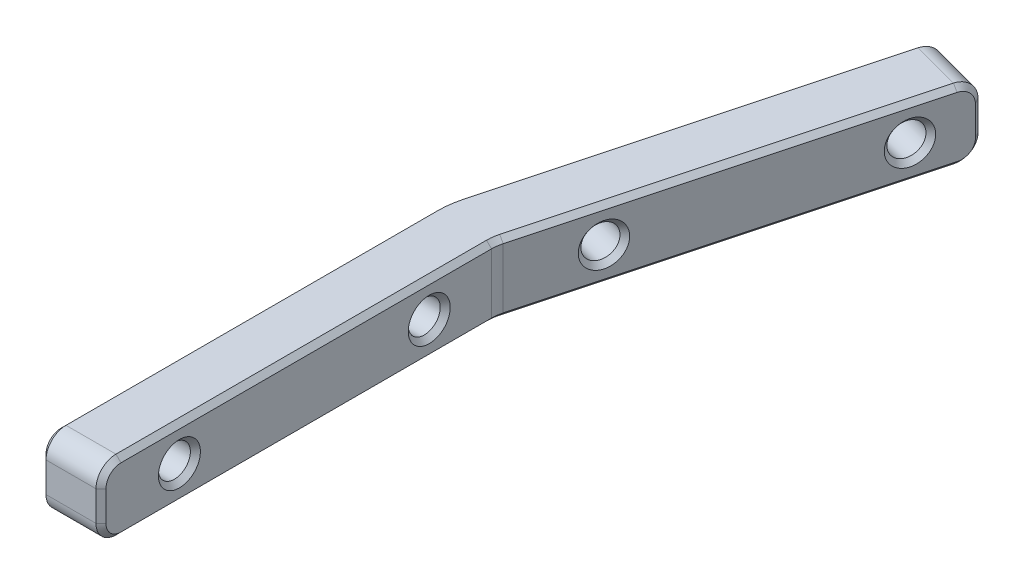
SolidWorks part; units mm, degrees
ref_plane "Front Plane" through (0, 0, 0) normal (0, 0, 1) x (1, 0, 0)
ref_plane "Top Plane" through (0, 0, 0) normal (0, 1, 0) x (1, 0, 0)
ref_plane "Right Plane" through (0, 0, 0) normal (1, 0, 0) x (0, 0, -1)
sketch "Sketch1" plane through (0, 0, 0) normal (0, 1, 0) x (1, 0, 0)
  line L0 (0, 0) -> (0, -50.8) construction
  line L1 (0, 0) -> (13.148, 49.069) construction
  line L2 (3.81, -0.5016) -> (3.81, -50.8)
  line L3 (3.81, -0.5016) -> (16.8282, 48.0829)
  line L4 (-3.81, 0.5016) -> (-3.81, -50.8)
  line L5 (-3.81, 0.5016) -> (9.4678, 50.0551)
  line L6 (3.81, -50.8) -> (-3.81, -50.8)
  line L7 (16.8282, 48.0829) -> (9.4678, 50.0551)
  dimension "D1" = 165
  dimension "D2" = 50.8
  dimension "D3" = 50.8
  dimension "D4" = 3.81
  dimension "D5" = 3.81
extrude "Boss-Extrude1" add sketch "Sketch1" along normal blind 8.89 contours L3 L7 L5 L4 L6 L2
sketch "Sketch2" plane through (3.81, 0, 0) normal (1, 0, 0) x (0, 0, -1)
  line L0 (-50.8, 4.445) -> (-0.5016, 4.445) construction
  line L1 (-50.8, 8.89) -> (-50.8, 0) construction
  line L2 (-0.5016, 8.89) -> (-0.5016, 0) construction
  circle A0 centre (-40.8334, 4.445) radius 2.032
  circle A1 centre (-9.0834, 4.445) radius 2.032
  dimension "D1" = 4.064
  dimension "D2" = 8.5818
  dimension "D3" = 31.75
extrude "Cut-Extrude1" cut sketch "Sketch2" against normal through all contours A1 | A0
sketch "Sketch3" plane through (3.6802, 0, 0.9861) normal (0.9659, 0, 0.2588) x (0.2588, 0, -0.9659)
  line L0 (0.5016, 4.445) -> (50.8, 4.445) construction
  line L1 (50.8, 8.89) -> (50.8, 0) construction
  circle A0 centre (43.3734, 4.445) radius 2.032
  circle A1 centre (11.6234, 4.445) radius 2.032
  dimension "D1" = 11.1218
  dimension "D3" = 4.064
  dimension "D2" = 31.75
extrude "Cut-Extrude2" cut sketch "Sketch3" against normal up to next contours A1 | A0
fillet "Fillet1" radius 2.54 4 edges at (13.148, 0, -49.069) (13.148, 8.89, -49.069) (0, 0, 50.8) (0, 8.89, 50.8)
fillet "Fillet2" radius 5.08 1 edges at (3.81, 4.445, 0.5016)
fillet "Fillet3" radius 11.43 1 edges at (-3.81, 4.445, -0.5016)
chamfer "Chamfer1" distance 0.635 angle 45 32 edges at (7.0198, 4.445, -40.9189) (-1.1977, 4.445, -10.2507) (-3.81, 4.445, 38.8014) (-3.81, 4.445, 7.0514) (-3.7122, 8.89, -0.4887) (2.6949, 8.89, -24.7784) (9.2753, 8.1461, -49.3365) (9.4678, 4.445, -50.0551) (9.2753, 0.7439, -49.3365) (-3.81, 8.89, 24.6316) (-3.81, 8.1461, 50.0561) (-3.81, 4.445, 50.8) (-3.81, 0.7439, 50.0561) (2.6949, 0, -24.7784) (-3.7122, 0, -0.4887) (-3.81, 0, 24.6316) (3.81, 4.445, 38.8014) (3.81, 4.445, 7.0514) (3.8535, 8.89, 0.5073) (3.81, 8.89, 24.7152) (3.81, 8.1461, 50.0561) (3.81, 4.445, 50.8) (3.81, 0.7439, 50.0561) (3.81, 0, 24.7152) (3.8535, 0, 0.5073) (10.0769, 0, -22.8869) (16.6356, 0.7439, -47.3643) (16.8282, 4.445, -48.0829) (16.6356, 8.1461, -47.3643) (10.0769, 8.89, -22.8869) (15.432, 4.445, -42.8722) (7.2145, 4.445, -12.204)
